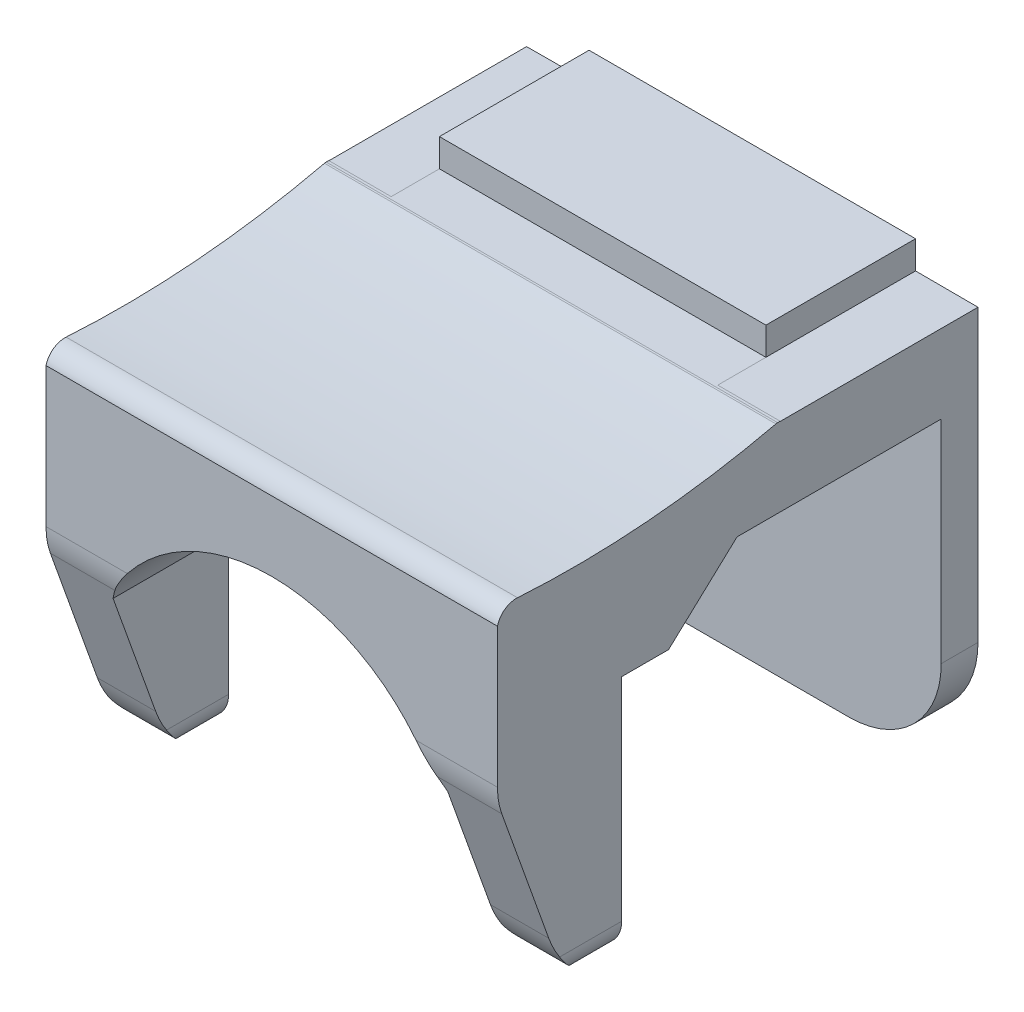
SolidWorks part; units mm, degrees
ref_plane "Front Plane" through (0, 0, 0) normal (0, 0, 1) x (1, 0, 0)
ref_plane "Top Plane" through (0, 0, 0) normal (0, 1, 0) x (1, 0, 0)
ref_plane "Right Plane" through (0, 0, 0) normal (1, 0, 0) x (0, 0, -1)
sketch "Sketch2" plane through (0, 0, 0) normal (1, 0, 0) x (0, 0, -1)
  line L0 (0, 15.5039) -> (-11.8, 15.5039)
  line L2 (-11.8, 15.5039) -> (-11.8, 13.3039)
  line L3 (-11.8, 13.3039) -> (-15.8, 13.3039)
  line L4 (-37.9, 10.4551) -> (-37.9, -0.5449)
  line L6 (-37.555, -2.5336) -> (-33.85, -12.8909)
  line L8 (-30.64, -16.8961) -> (-28.1, -16.8961)
  line L9 (-28.1, -16.8961) -> (-28.1, 2.1039)
  line L10 (-28.1, 2.1039) -> (-24.4, 2.1039)
  line L11 (-24.4, 2.1039) -> (-19, 7.1039)
  line L12 (-19, 7.1039) -> (-2.9, 7.1039)
  line L13 (-2.9, 7.1039) -> (-2.9, -16.8961)
  line L14 (-2.9, -16.8961) -> (0, -16.8961)
  line L15 (0, -16.8961) -> (0, 15.5039)
  line L16 (-52.3771, -16.8961) -> (2.3233, -16.8961) construction
  line L18 (0, -21.9846) -> (0, 18.7879) construction
  line L19 (4.7908, 15.5039) -> (-43.4718, 15.5039) construction
  line L20 (-37.9, -19.4529) -> (-37.9, 20.5271) construction
  arc A0 (-15.8, 13.3039) -> (-15.938, 13.288) centre (-15.8, 12.695) ccw
  arc A1 (-15.938, 13.288) -> (-36.3141, 11.6039) centre (-31.8472, 81.6649) cw
  arc A2 (-36.3141, 11.6039) -> (-37.9, 10.4551) centre (-36.4119, 10.0699) ccw
  arc A3 (-37.9, -0.5449) -> (-37.555, -2.5336) centre (-31.9956, -0.5449) ccw
  arc A4 (-33.85, -12.8909) -> (-30.64, -16.8961) centre (-26.4381, -10.2395) ccw
  dimension "D10" = 19
  dimension "D1" = 9.8
  dimension "D2" = 5.75
  dimension "D3" = 13.5
  dimension "D4" = 2.2
  dimension "D5" = 18.9
  dimension "D6" = 5
  dimension "D7" = 35
  dimension "D9" = 4
  dimension "D11" = 28.5
  dimension "D12" = 11
  dimension "D13" = 11
  dimension "D14" = 2.54
  dimension "D15" = 11.8
extrude "Boss-Extrude2" add sketch "Sketch2" along normal mid plane 35.6
sketch "Sketch3" plane through (0, 0, 37.9) normal (0, 0, 1) x (1, 0, 0)
  line L0 (-13.2, -16.8961) -> (-13.2, -3.4961)
  line L1 (17.8, -16.8961) -> (-17.8, -16.8961) construction
  line L2 (13.2, -3.4961) -> (13.2, -16.8961)
  line L4 (17.8, -2.5336) -> (17.8, -12.8909) construction
  line L5 (-17.8, -2.5336) -> (-17.8, -12.8909) construction
  line L6 (17.8, 10.4551) -> (17.8, -0.5449) construction
  line L7 (-17.8, 4.9551) -> (17.8, 4.9551) construction
  line L8 (-17.8, 10.4551) -> (-17.8, -0.5449) construction
  line L10 (17.8, 11.607) -> (-17.8, 11.607) construction
  line L11 (-17.8, -14.5961) -> (-17.8, -16.8961)
  line L12 (-17.8, -16.8961) -> (17.8, -16.8961)
  line L13 (17.8, -16.8961) -> (17.8, -14.5961)
  line L15 (-12.875, 15.5039) -> (12.875, 15.5039) construction
  line L16 (17.8, 15.5039) -> (-17.8, 15.5039) construction
  line L17 (-12.875, 15.5039) -> (-12.875, 13.3039)
  line L18 (-12.875, 13.3039) -> (-17.8, 13.288)
  line L19 (-17.8, 13.288) -> (-17.8, 15.5039)
  line L20 (-17.8, 15.5039) -> (-12.875, 15.5039)
  line L21 (12.875, 15.5039) -> (17.8, 15.5039)
  line L22 (17.8, 15.5039) -> (17.8, 13.288)
  line L23 (17.8, 13.288) -> (12.875, 13.3039)
  line L24 (17.8, 13.3039) -> (-17.8, 13.3039) construction
  line L25 (12.875, 13.3039) -> (12.875, 15.5039)
  arc A0 (-13.2, -3.4961) -> (0, 4.9551) centre (0, -9.5791) cw
  arc A1 (0, 4.9551) -> (13.2, -3.4961) centre (0, -9.5791) cw
  circle A2 centre (15.5, -14.5961) radius 2.3 construction
  circle A3 centre (-15.5, -14.5961) radius 2.3 construction
  arc A4 (-13.2, -14.5961) -> (-15.5, -16.8961) centre (-15.5, -14.5961) cw
  arc A5 (-15.5, -16.8961) -> (-17.8, -14.5961) centre (-15.5, -14.5961) cw
  arc A6 (17.8, -14.5961) -> (15.5, -16.8961) centre (15.5, -14.5961) cw
  arc A7 (15.5, -16.8961) -> (13.2, -14.5961) centre (15.5, -14.5961) cw
  point P15 (0, 4.9551)
  point P47 (0, 15.5039)
  point P48 (0, 15.5039)
  point P57 (-12.875, 13.3039)
  point P58 (0, 0)
  line M6 (-17.8, -0.5449) -> (17.8, -0.5449)
  dimension "D1" = 4.6
  dimension "D2" = 4.6
  dimension "D3" = 13.4
  dimension "D4" = 13.4
  dimension "D5" = 6.6519
  dimension "D6" = 25.75
extrude "Cut-Extrude1" cut sketch "Sketch3" against normal blind 15.6 contours A1 A0 L0 L12 L2 M6 | A1 A0 M6 | L0 A4 L12 | L12 A5 L11 | L12 A7 L2 | L13 A6 L12
sketch "Sketch4" plane through (0, 0, 0) normal (0, 0, 1) x (1, 0, 0)
  line L0 (-12.875, 15.5039) -> (12.875, 15.5039) construction
  line L1 (-12.875, 15.5039) -> (-12.875, 13.3039)
  line L2 (-12.875, 13.3039) -> (-17.8, 13.288)
  line L3 (-17.8, 13.288) -> (-17.8, 15.5039)
  line L4 (-17.8, 15.5039) -> (-12.875, 15.5039)
  line L5 (12.875, 15.5039) -> (17.8, 15.5039)
  line L6 (17.8, 15.5039) -> (17.8, 13.288)
  line L7 (17.8, 13.288) -> (12.875, 13.3039)
  line L8 (12.875, 13.3039) -> (12.875, 15.5039)
  line L9 (17.8, 15.5039) -> (-17.8, 15.5039) construction
  line L10 (-10.5084, -16.8961) -> (10.5084, -16.8961) construction
  line L11 (17.8, -16.8961) -> (-17.8, -16.8961) construction
  line L12 (17.8, -2.5336) -> (17.8, -12.8909) construction
  line L13 (17.8, -9.6045) -> (17.8, -16.8961)
  line L14 (17.8, -16.8961) -> (10.5084, -16.8961)
  line L15 (-17.8, -2.5336) -> (-17.8, -12.8909) construction
  line L16 (-17.8, -9.6045) -> (-17.8, -16.8961)
  line L17 (-17.8, -16.8961) -> (-10.5084, -16.8961)
  arc A0 (10.5084, -16.8961) -> (17.8, -9.6045) centre (10.5084, -9.6045) ccw
  arc A1 (-10.5084, -16.8961) -> (-17.8, -9.6045) centre (-10.5084, -9.6045) cw
  point P6 (0, 15.5039)
  point P11 (0, 15.5039)
  point P14 (0, -16.8961)
  point P17 (0, -16.8961)
extrude "Cut-Extrude2" cut sketch "Sketch4" along normal blind 15.6
